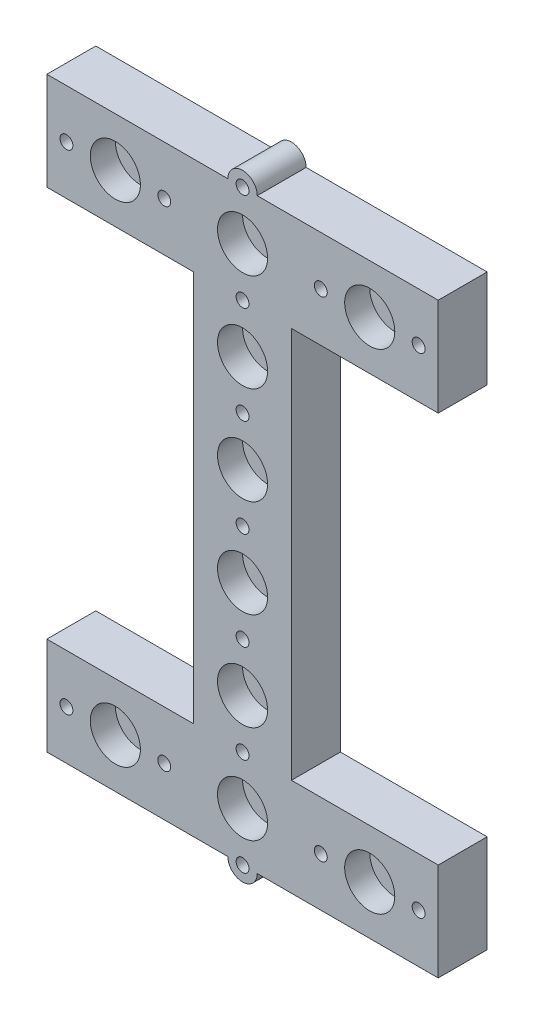
SolidWorks part; units mm, degrees
material "ABS"
ref_plane "Front Plane" through (0, 0, 0) normal (0, 0, 1) x (1, 0, 0)
ref_plane "Top Plane" through (0, 0, 0) normal (0, 1, 0) x (1, 0, 0)
ref_plane "Right Plane" through (0, 0, 0) normal (1, 0, 0) x (0, 0, -1)
sketch "Base" plane through (0, 0, 0) normal (0, 0, 1) x (1, 0, 0)
  line L0 (-25, 100) -> (-25, -100)
  line L1 (25, 100) -> (-25, 100) construction
  line L2 (25, 100) -> (25, -100) construction
  line L3 (25, -100) -> (-25, -100) construction
  line L4 (-25, 100) -> (-25, -100) construction
  line L5 (25, 100) -> (-25, -100) construction
  line L6 (25, -100) -> (-25, 100) construction
  line L7 (100, 150) -> (-100, 150) construction
  line L8 (100, 150) -> (100, -150) construction
  line L9 (100, -150) -> (-100, -150) construction
  line L10 (-100, 150) -> (-100, -150) construction
  line L11 (100, 150) -> (-100, -150) construction
  line L12 (100, -150) -> (-100, 150) construction
  line L13 (-25, -100) -> (-100, -100)
  line L14 (-100, -100) -> (-100, -150)
  line L16 (100, -150) -> (100, -100)
  line L17 (100, -100) -> (25, -100)
  line L18 (25, -100) -> (25, 100)
  line L19 (25, 100) -> (100, 100)
  line L20 (100, 100) -> (100, 150)
  line L22 (-100, 150) -> (-100, 100)
  line L23 (-100, 100) -> (-25, 100)
  line L24 (-100, 150) -> (-7.5, 150)
  line L25 (-7.5, -150) -> (7.5, -150) construction
  line L26 (-7.5, -150) -> (-7.5, -165) construction
  line L27 (-7.5, -165) -> (7.5, -165) construction
  line L28 (7.5, -150) -> (7.5, -165) construction
  line L29 (-7.5, 150) -> (7.5, 150) construction
  line L30 (-7.5, 150) -> (-7.5, 165) construction
  line L31 (-7.5, 165) -> (7.5, 165) construction
  line L32 (7.5, 150) -> (7.5, 165) construction
  line L36 (7.5, 150) -> (100, 150)
  line L37 (-100, -150) -> (-7.5, -150)
  line L41 (7.5, -150) -> (100, -150)
  arc A0 (-7.5, 150) -> (7.5, 150) centre (0, 150) cw
  arc A1 (7.5, -150) -> (-7.5, -150) centre (0, -150) cw
  point P0 (0, 0)
  point P6 (0, 0)
  point P19 (0, -165)
  point P24 (0, 165)
  dimension "D1" = 50
  dimension "D2" = 200
  dimension "D3" = 300
  dimension "D4" = 200
  dimension "D5" = 15
  dimension "D6" = 15
  dimension "D7" = 15
extrude "HalfBody" add sketch "Base" along normal blind 25
sketch "CornerHolesGuide" plane through (0, 0, 25) normal (0, 0, 1) x (1, 0, 0)
  line L1 (-100, 150) -> (-100, 100) construction
  circle A0 centre (-65, 125) radius 12.8
  point P6 (-100, 125)
  dimension "D1" = 25.6
  dimension "D2" = 35
extrude "CornerHoles" cut sketch "CornerHolesGuide" against normal blind 12.8
pattern_linear "PatternCornerHoles" count 2 spacing 130 along (1, 0, 0) count 2 spacing 250 along (0, -1, 0) of "CornerHoles"
sketch "CenterHolesGuide" plane through (0, 0, 25) normal (0, 0, 1) x (1, 0, 0)
  line L0 (-100, 150) -> (-100, 100) construction
  circle A0 centre (0, 125) radius 12.8
  circle A1 centre (-65, 125) radius 12.8 construction
  point P10 (-100, 125)
extrude "CenterHoles" cut sketch "CenterHolesGuide" against normal blind 12.8 contours A0
pattern_linear "PatternCenterHoles" count 6 spacing 50 along (0, -1, 0) of "CenterHoles"
sketch "BoltsHolesGuide" plane through (0, 0, 25) normal (0, 0, 1) x (1, 0, 0)
  line L0 (-100, 150) -> (-100, 100) construction
  line L1 (-100, -100) -> (-100, -150) construction
  line L2 (100, 100) -> (100, 150) construction
  line L3 (100, -150) -> (100, -100) construction
  circle A0 centre (0, 125) radius 12.8 construction
  circle A1 centre (-65, 125) radius 12.8 construction
  circle A2 centre (65, 125) radius 12.8 construction
  point P0 (0, 150)
  point P3 (90, 125)
  point P6 (0, 100)
  point P7 (0, 50)
  point P8 (0, 0)
  point P9 (0, -50)
  point P10 (0, -100)
  point P11 (0, -150)
  point P12 (-90, 125)
  point P14 (-100, 125)
  point P19 (-40, 125)
  point P20 (-40, -125)
  point P21 (-90, -125)
  point P25 (-100, -125)
  point P28 (40, 125)
  point P29 (40, -125)
  point P30 (90, -125)
  point P31 (100, 125)
  point P36 (100, -125)
  dimension "D1" = 25
  dimension "D3" = 50
  dimension "D4" = 25
  dimension "D7" = 50
  dimension "D8" = 25
  dimension "D11" = 50
  dimension "D2" = 7
  dimension "D5" = 2
  dimension "D6" = 2
  dimension "D9" = 2
  dimension "D10" = 2
hole_wizard "CBORE for M6 SHCS1" positions "Sketch1" profile "Sketch2" counterbore size "M6" standard "ANSI Metric" end condition through all
sketch "Sketch1" plane through (0, 0, 0) normal (0, 0, -1) x (-1, 0, 0)
  point P0 (-90, 125)
  point P3 (-40, 125)
  point P6 (0, 150)
  point P9 (40, 125)
  point P12 (90, 125)
  point P15 (0, 50)
  point P18 (0, 0)
  point P21 (0, -50)
  point P24 (0, -100)
  point P27 (-90, -125)
  point P30 (-40, -125)
  point P33 (40, -125)
  point P36 (90, -125)
  point P39 (0, -150)
  point P43 (0, 100)
sketch "Sketch2" plane through (90, 125, 0) normal (1, 0, 0) x (0, 1, 0)
  line L0 (0, 0) -> (0, 25)
  line L1 (0, 25) -> (3.3, 25)
  line L3 (3.3, 25) -> (3.3, 6)
  line L4 (3.3, 6) -> (5.9, 6)
  line L5 (5.9, 6) -> (5.9, 0)
  line L7 (5.9, 0) -> (0, 0)
  line L11 (0, -6.35) -> (0, 107.95) construction
  dimension "Thru Hole Dia." = 6.6
  dimension "Thru Hole Depth" = 25
  dimension "C'Bore Dia." = 11.8
  dimension "C'Bore Depth" = 6
